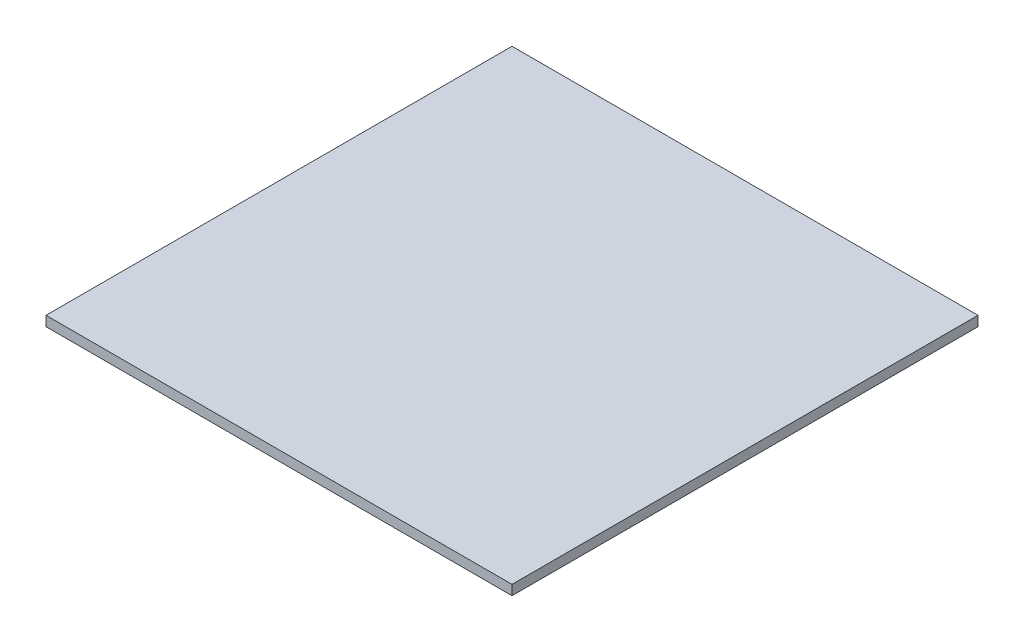
SolidWorks part; units mm, degrees
ref_plane "Front Plane" through (0, 0, 0) normal (0, 0, 1) x (1, 0, 0)
ref_plane "Top Plane" through (0, 0, 0) normal (0, 1, 0) x (1, 0, 0)
ref_plane "Right Plane" through (0, 0, 0) normal (1, 0, 0) x (0, 0, -1)
sketch "Sketch1" plane through (0, 0, 0) normal (0, 1, 0) x (1, 0, 0)
  line L1 (-150, -150) -> (150, -150)
  line L2 (-150, -150) -> (-150, 150)
  line L3 (-150, 150) -> (150, 150)
  line L4 (150, -150) -> (150, 150)
  line L5 (-150, -150) -> (150, 150) construction
  line L6 (-150, 150) -> (150, -150) construction
  point P0 (0, 0)
  dimension "D1" = 300
  dimension "D2" = 300
extrude "Boss-Extrude1" add sketch "Sketch1" along normal blind 6.35
